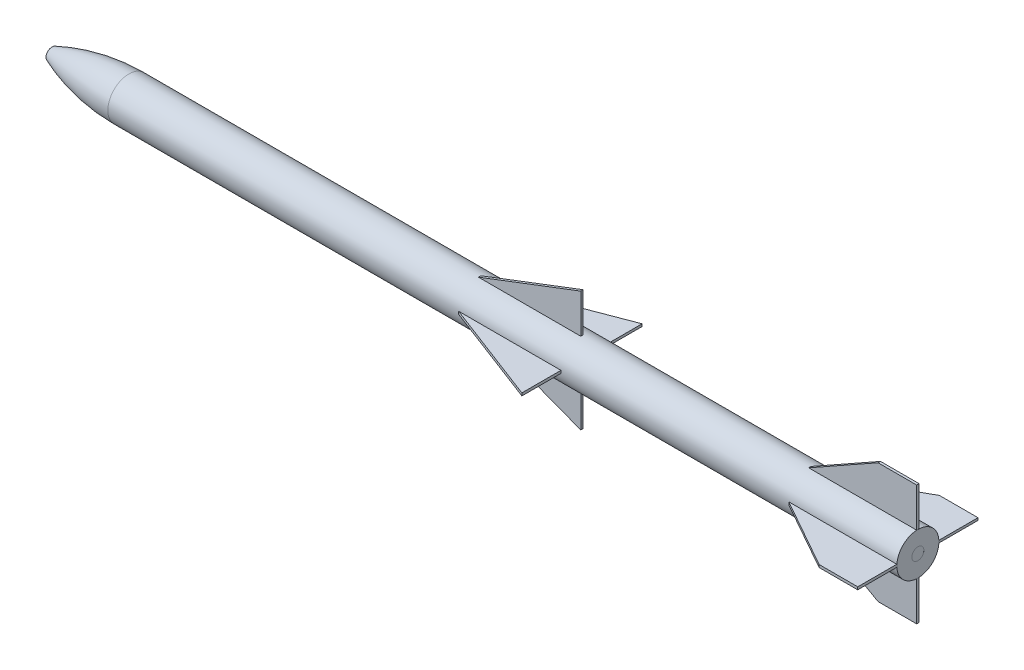
SolidWorks part; units mm, degrees
ref_plane "Front Plane" through (0, 0, 0) normal (0, 0, 1) x (1, 0, 0)
ref_plane "Top Plane" through (0, 0, 0) normal (0, 1, 0) x (1, 0, 0)
ref_plane "Right Plane" through (0, 0, 0) normal (1, 0, 0) x (0, 0, -1)
sketch "Sketch1" plane through (0, 0, 0) normal (0, 0, 1) x (1, 0, 0)
  line L0 (0, 0) -> (3657.6, 0)
  line L1 (22.9554, 384.3947) -> (280.2887, 384.3947) construction
  line L2 (324.708, 63.5) -> (3657.6, 63.5)
  line L3 (3657.6, 63.5) -> (3657.6, 0)
  line L4 (480.9169, 63.5) -> (480.9169, 0)
  line L5 (571.1736, 63.5) -> (571.1736, 0)
  line L6 (950.2989, 63.5) -> (950.2989, 0)
  line L7 (1010.4581, 63.5) -> (1010.4581, 0)
  line L8 (1537.4239, 63.5) -> (1537.4239, 0)
  line L9 (1569.7162, 63.5) -> (1569.7162, 0)
  line L10 (2174.1007, 63.5) -> (2174.1007, 0)
  line L11 (2213.5717, 63.5) -> (2213.5717, 0)
  line L12 (2925.9617, 63.5) -> (2925.9617, 0)
  line L13 (2960.8411, 63.5) -> (2960.8411, 0)
  line L14 (3159.8585, 63.5) -> (3159.8585, 0)
  line L15 (3475.918, 63.5) -> (3475.918, 0)
  line L16 (3505.578, 63.5) -> (3505.578, 0)
  line L17 (3626.4996, 63.5) -> (3626.4996, 0)
  line L18 (3626.4996, -25.4) -> (0, -25.4) construction
  arc A1 (324.708, 63.5) -> (0, 0) centre (324.708, -798.4493) ccw
  dimension "D1" = 3657.6
  dimension "D2" = 63.5
  dimension "D3" = 25.4
revolve "Revolve-Thin10" add sketch "Sketch1" angle 360 about L18
sketch "Sketch2" plane through (3657.6025, 0, 0) normal (1, 0, 0) x (0, 0, -1)
  circle A0 centre (0, -25.4) radius 88.7876
sketch "Sketch4" plane through (0, 0, 0) normal (0, 1, 0) x (1, 0, 0)
  line L0 (3657.6025, 0) -> (3657.6025, 254)
  line L1 (3657.6025, -88.9025) -> (3657.6025, 88.9025) construction
  line L2 (3657.6025, 0) -> (3657.6025, -254)
  line L3 (3657.6025, 254) -> (3494.6199, 254)
  line L4 (3494.6199, 254) -> (3201.4381, 88.9025)
  line L5 (3657.6025, 88.9025) -> (324.708, 88.9025) construction
  line L6 (3201.4381, 88.9025) -> (3657.6025, 88.9025)
  line L7 (3657.6025, -254) -> (3494.6199, -254)
  line L8 (3494.6199, -254) -> (3201.4381, -88.9025)
  line L9 (324.708, -88.9025) -> (3657.6025, -88.9025) construction
  line L10 (3201.4381, -88.9025) -> (3657.6025, -88.9025)
  dimension "D1" = 254
  dimension "D2" = 254
extrude "Boss-Extrude2" add sketch "Sketch4" against normal blind 50.8 separate body contours L4 L6 L0 L3 | L10 L8 L7 L2
sketch "Sketch8" plane through (3657.6025, 0, 0) normal (1, 0, 0) x (0, 0, -1)
  line L0 (88.9025, -25.4) -> (88.9025, -20.4033)
  line L1 (88.9025, -50.8) -> (88.9025, 0) construction
  line L2 (88.9025, -20.4033) -> (254, -20.4033)
  line L3 (254, -50.8) -> (254, 0) construction
  line L4 (254, -20.4033) -> (254, -30.4908)
  line L5 (254, -30.4908) -> (88.7567, -30.4908)
  line L6 (88.7567, -30.4908) -> (88.9025, -20.4033)
  circle A0 centre (0, -25.4) radius 88.9025 construction
  line M1 (254, 0) -> (88.9025, 0)
  line M2 (88.9025, 0) -> (88.9025, -50.8)
  line M3 (88.9025, -50.8) -> (254, -50.8)
  line M4 (254, -50.8) -> (254, 0)
extrude "Cut-Extrude1" cut sketch "Sketch8" against normal blind 762 contours L2 M2 M4 M1 | L5 M4 M2 M3
sketch "Sketch15" plane through (3657.6025, 0, 0) normal (1, 0, 0) x (0, 0, -1)
  line L0 (-88.9025, -30.3911) -> (-254, -30.3911)
  line L1 (-88.9025, -50.8) -> (-88.9025, 0) construction
  line L2 (-254, -50.8) -> (-254, 0) construction
  line L3 (-254, -30.3911) -> (-254, -19.2526)
  line L4 (-254, -19.2526) -> (-88.9025, -19.2526)
  line L5 (-88.9025, -19.2526) -> (-88.9025, -30.3911)
extrude "Cut-Extrude4" cut sketch "Sketch15" against normal blind 762 flip side to cut
sketch "Sketch18" plane through (0, 0, 0) normal (0, 1, 0) x (1, 0, 0)
  line L0 (0, 0) -> (3657.6025, 0) construction
  line L1 (3657.6025, -88.9025) -> (3657.6025, 88.9025) construction
  line L2 (3657.6025, 88.9025) -> (3657.6025, 254) construction
ref_plane "Plane1" through (-0.013, 0, 0) normal (1, 0, 0) x (0, 0, -1)
sketch "Sketch19" plane through (-0.013, 0, 0) normal (1, 0, 0) x (0, 0, -1)
  circle A0 centre (0, -25.4) radius 25.3975
extrude "Boss-Extrude3" add sketch "Sketch19" along normal blind 3657.6
sketch "Sketch20" plane through (0, 0, 0) normal (0, 0, 1) x (1, 0, 0)
  line L0 (3657.6025, -25.4) -> (3657.6025, 228.6)
  line L1 (3657.6025, -114.1876) -> (3657.6025, 63.3876) construction
  line L2 (3657.6025, 228.6) -> (3494.6199, 228.6)
  line L3 (3494.6199, 228.6) -> (3201.4381, 63.5025)
  line L4 (3657.6025, 63.5025) -> (324.708, 63.5025) construction
  line L5 (3201.4381, 63.5025) -> (3657.6025, 63.5025)
  line L6 (3657.6025, -279.4) -> (3657.6025, -25.4)
  line L7 (3657.6025, -279.4) -> (3494.6199, -279.4)
  line L8 (3494.6199, -279.4) -> (3201.4381, -114.3025)
  line L9 (324.708, -114.3025) -> (3657.6025, -114.3025) construction
  line L10 (3201.4381, -114.3025) -> (3657.6025, -114.3025)
  dimension "D1" = 254
extrude "Boss-Extrude4" add sketch "Sketch20" along normal mid plane 10.16 separate body contours L3 L5 L0 L2 | L10 L8 L7 L6
sketch "Sketch24" plane through (0, 0, 0) normal (0, 0, 1) x (1, 0, 0)
  line L0 (1806.3601, 63.5025) -> (2238.6581, 228.6)
  line L1 (3657.6025, 63.5025) -> (324.708, 63.5025) construction
  line L2 (2238.6581, 228.6) -> (2238.6581, -279.4)
  line L3 (2238.6581, -279.4) -> (1806.3601, -114.3025)
  line L4 (324.708, -114.3025) -> (3657.6025, -114.3025) construction
  line L5 (1806.3601, -114.3025) -> (2238.6581, -114.3025)
  line L6 (1806.3601, 63.5025) -> (2238.6581, 63.5025)
  line L7 (1806.3601, 63.5025) -> (1806.3601, -114.3025)
  line L8 (1806.3601, -25.4) -> (2238.6581, -25.4)
  dimension "D1" = 508
  dimension "D2" = 254
extrude "Boss-Extrude5" add sketch "Sketch24" along normal mid plane 10.16 separate body contours L0 L6 L2 | L5 L3 L2
sketch "Sketch25" plane through (0, 0, 0) normal (0, 1, 0) x (1, 0, 0)
  line L0 (2238.8126, 0) -> (2238.8126, 254)
  line L1 (0, 0) -> (3657.6025, 0) construction
  line L2 (2238.8126, 254) -> (1806.3601, 88.9025)
  line L3 (3657.6025, 88.9025) -> (324.708, 88.9025) construction
  line L4 (1806.3601, 88.9025) -> (2238.8126, 88.9025)
  line L5 (2238.8126, 0) -> (2238.8126, -254)
  line L6 (2238.8126, -254) -> (1806.3601, -88.9025)
  line L7 (324.708, -88.9025) -> (3657.6025, -88.9025) construction
  line L8 (1806.3601, -88.9025) -> (2238.8126, -88.9025)
  dimension "D1" = 254
  dimension "D2" = 254
extrude "Boss-Extrude6" add sketch "Sketch25" against normal blind 50.8 separate body contours L2 L4 L0 | L8 L6 L5
sketch "Sketch26" plane through (2238.8126, 0, 0) normal (1, 0, 0) x (0, 0, -1)
  line L0 (88.9025, -20.4033) -> (254, -20.4033)
  line L1 (254, -20.4033) -> (254, -30.4908)
  line L2 (254, -50.8) -> (254, 0) construction
  line L3 (254, -30.4908) -> (88.9025, -30.4908) construction
  line L4 (254, -30.4908) -> (88.9025, -30.4908)
  line L5 (88.9025, -30.4908) -> (88.9025, -20.4033)
extrude "Cut-Extrude7" cut sketch "Sketch26" against normal blind 508 flip side to cut
sketch "Sketch32" plane through (2238.8126, 0, 0) normal (1, 0, 0) x (0, 0, -1)
  line L0 (-254, -19.2526) -> (-254, -30.3911)
  line L1 (-254, -30.3911) -> (-88.9025, -30.3911)
  line L2 (-88.9025, -50.8) -> (-88.9025, 0) construction
  line L3 (-254, -30.3911) -> (-88.9025, -30.3911) construction
  line L4 (-88.9025, -30.3911) -> (-88.9025, -19.2526)
  line L5 (-88.9025, -19.2526) -> (-254, -19.2526)
extrude "Cut-Extrude16" cut sketch "Sketch32" against normal blind 508 flip side to cut
